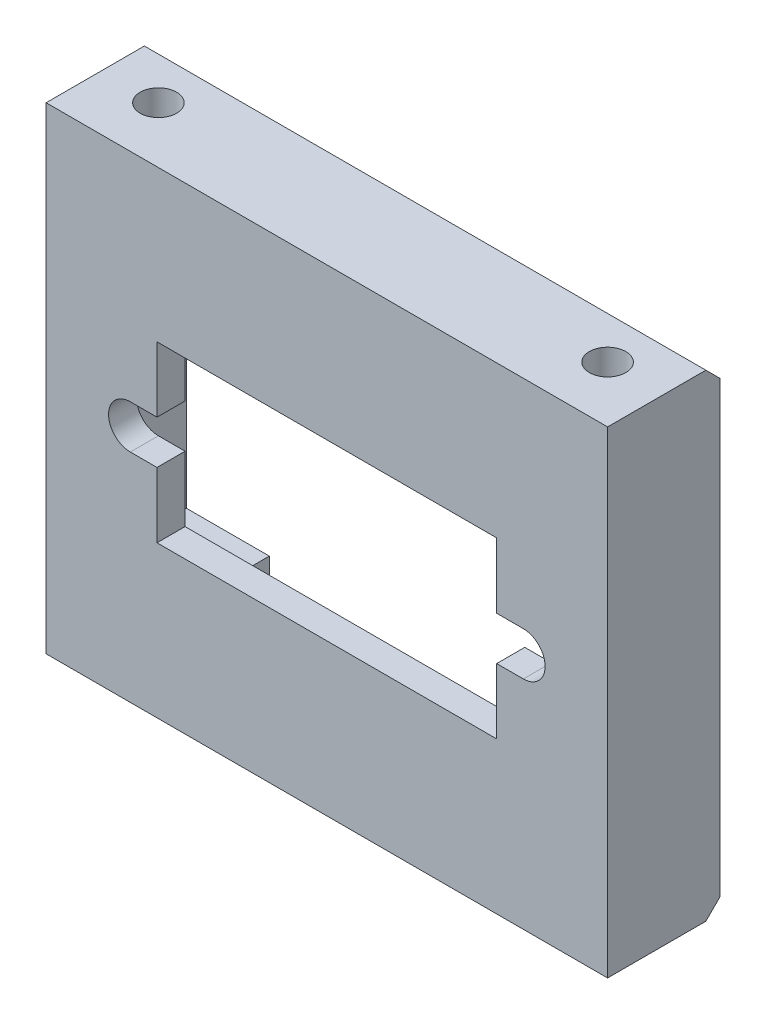
SolidWorks part; units mm, degrees
ref_plane "正面" through (0, 0, 0) normal (0, 0, 1) x (1, 0, 0)
ref_plane "平面" through (0, 0, 0) normal (0, 1, 0) x (1, 0, 0)
ref_plane "右側面" through (0, 0, 0) normal (1, 0, 0) x (0, 0, -1)
sketch "ｽｹｯﾁ1" plane through (0, 0, 0) normal (0, 0, 1) x (1, 0, 0)
  line L1 (-20, 17) -> (20, 17)
  line L2 (-20, 17) -> (-20, -17)
  line L3 (-20, -17) -> (20, -17)
  line L4 (20, 17) -> (20, -17)
  line L5 (-20, 17) -> (20, -17) construction
  line L6 (-20, -17) -> (20, 17) construction
  point P0 (0, 0)
  dimension "D1" = 34
  dimension "D2" = 40
extrude "ﾎﾞｽ - 押し出し1" add sketch "ｽｹｯﾁ1" along normal blind 2
sketch "ｽｹｯﾁ2" plane through (0, 0, 2) normal (0, 0, 1) x (1, 0, 0)
  line L5 (-12.1, 6.2) -> (12.1, 6.2)
  line L6 (-12.1, 6.2) -> (-12.1, -6.2)
  line L15 (-14, 1.55) -> (14, 1.55)
  line L16 (-14, 1.55) -> (-14, -1.55)
  line L17 (-14, -1.55) -> (14, -1.55)
  line L18 (14, 1.55) -> (14, -1.55)
  line L19 (-14, 1.55) -> (14, -1.55) construction
  line L20 (-14, -1.55) -> (14, 1.55) construction
  line L21 (-12.1, -6.2) -> (12.1, -6.2)
  line L22 (12.1, 6.2) -> (12.1, -6.2)
  line L23 (-12.1, 6.2) -> (12.1, -6.2) construction
  line L24 (-12.1, -6.2) -> (12.1, 6.2) construction
  arc A0 (14, 1.55) -> (14, -1.55) centre (14, 0) cw
  arc A1 (-14, 1.55) -> (-14, -1.55) centre (-14, 0) ccw
  point P0 (0, 0)
  point P1 (0, 0)
  dimension "D1" = 12.4
  dimension "D2" = 24.2
  dimension "D3" = 3.1
  dimension "D4" = 1.9
extrude "ｶｯﾄ - 押し出し1" cut sketch "ｽｹｯﾁ2" against normal blind 2 contours L15 L22 L17 L18 | L16 L17 L6 L15 | A0 L18 | L16 A1
sketch "ｽｹｯﾁ3" plane through (0, 0, 0) normal (0, 0, -1) x (-1, 0, 0)
  line L0 (20, 17) -> (20, -17) construction
  line L1 (20, 17) -> (18, 17)
  line L2 (20, 17) -> (20, -17)
  line L3 (20, -17) -> (18, -17)
  line L4 (18, 17) -> (18, -17)
  line L5 (20, -17) -> (-20, -17) construction
  line L7 (-20, 17) -> (-18, 17)
  line L8 (-20, 17) -> (-20, -17)
  line L9 (-20, -17) -> (-18, -17)
  line L10 (-18, 17) -> (-18, -17)
  dimension "D1" = 2
extrude "ﾎﾞｽ - 押し出し2" add sketch "ｽｹｯﾁ3" along normal blind 6
sketch "ｽｹｯﾁ5" plane through (0, 0, 0) normal (0, 0, -1) x (-1, 0, 0)
  line L0 (-18, -17) -> (-18, 17) construction
  line L1 (-18, 17) -> (18, 17)
  line L2 (-18, 17) -> (-18, 15.02)
  line L3 (-18, 15.02) -> (18, 15.02)
  line L4 (18, 17) -> (18, 15.02)
  line L5 (-18, 17) -> (18, 17) construction
  line L6 (18, 17) -> (18, -17) construction
  line L11 (-18, -17) -> (18, -17)
  line L12 (-18, -17) -> (-18, -15.02)
  line L13 (-18, -15.02) -> (18, -15.02)
  line L14 (18, -17) -> (18, -15.02)
  dimension "D2" = 1.98
extrude "ﾎﾞｽ - 押し出し3" add sketch "ｽｹｯﾁ5" along normal up to surface (6 mm away) up to face at (19, 0, -6)
sketch "ｽｹｯﾁ6" plane through (0, 0, 0) normal (0, 0, -1) x (-1, 0, 0)
  line L0 (-18, -15.02) -> (-18, 15.02) construction
  line L1 (-18, 15.02) -> (-12.1, 15.02)
  line L2 (-18, 15.02) -> (-18, 11.02)
  line L3 (-18, 11.02) -> (-12.1, 11.02)
  line L4 (-12.1, 15.02) -> (-12.1, 11.02)
  line L5 (-18, -15.02) -> (-18, 15.02) construction
  line L6 (-12.1, 6.2) -> (-12.1, 1.55) construction
  line L7 (18, 15.02) -> (18, -15.02) construction
  line L8 (18, 15.02) -> (12.1, 15.02)
  line L9 (18, 15.02) -> (18, 11.02)
  line L10 (18, 11.02) -> (12.1, 11.02)
  line L11 (12.1, 15.02) -> (12.1, 11.02)
  line L12 (18, 15.02) -> (18, -15.02) construction
  line L13 (12.1, 6.2) -> (12.1, 1.55) construction
  line L14 (12.1, -1.55) -> (12.1, -6.2) construction
  line L15 (18, -15.02) -> (12.1, -15.02)
  line L16 (18, -15.02) -> (18, -11.02)
  line L17 (18, -11.02) -> (12.1, -11.02)
  line L18 (12.1, -15.02) -> (12.1, -11.02)
  line L19 (-12.1, -1.55) -> (-12.1, -6.2) construction
  line L20 (-18, -15.02) -> (-12.1, -15.02)
  line L21 (-18, -15.02) -> (-18, -11.02)
  line L22 (-18, -11.02) -> (-12.1, -11.02)
  line L23 (-12.1, -15.02) -> (-12.1, -11.02)
  line L26 (-18, 15.02) -> (18, 15.02) construction
  line L27 (-18, 15.02) -> (18, 15.02) construction
  dimension "D1" = 4
extrude "ﾎﾞｽ - 押し出し4" add sketch "ｽｹｯﾁ6" along normal up to surface (6 mm away)
sketch "ｽｹｯﾁ7" plane through (0, 17, 0) normal (0, 1, 0) x (1, 0, 0)
  line L0 (-20, 2) -> (20, 2) construction
  line L1 (-20, -2) -> (-20, 6) construction
  line L2 (20, -2) -> (20, 6) construction
  circle A0 centre (-16, 2) radius 1.3
  circle A1 centre (16, 2) radius 1.3
  dimension "D1" = 2.6
  dimension "D2" = 4
  dimension "D3" = 4
extrude "ｶｯﾄ - 押し出し2" cut sketch "ｽｹｯﾁ7" against normal through all
chamfer "面取り1" distance 1 angle 45 2 edges at (0, 17, -6) (0, -17, -6)
